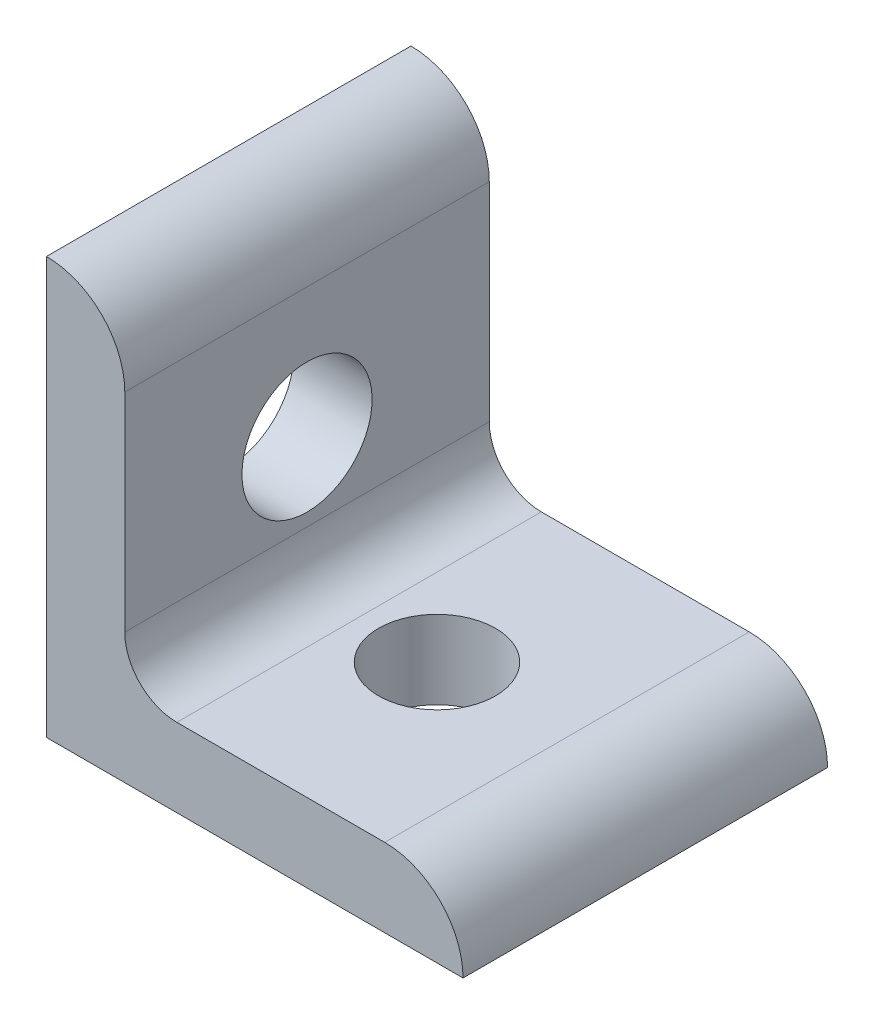
SolidWorks part; units mm, degrees
ref_plane "Front Plane" through (0, 0, 0) normal (0, 0, 1) x (1, 0, 0)
ref_plane "Top Plane" through (0, 0, 0) normal (0, 1, 0) x (1, 0, 0)
ref_plane "Right Plane" through (0, 0, 0) normal (1, 0, 0) x (0, 0, -1)
sketch "Sketch1" plane through (0, 0, 0) normal (0, 0, 1) x (1, 0, 0)
  line L0 (0, 0) -> (0, 25.4)
  line L1 (4.7752, 20.6248) -> (4.7752, 25.4) construction
  line L2 (4.7752, 20.6248) -> (4.7752, 7.9502)
  line L3 (7.9502, 4.7752) -> (20.6248, 4.7752)
  line L4 (4.7752, 25.4) -> (0, 25.4) construction
  line L5 (25.4, 0) -> (0, 0)
  line L6 (20.6248, 4.7752) -> (25.4, 4.7752) construction
  line L7 (25.4, 4.7752) -> (25.4, 0) construction
  arc A0 (4.7752, 20.6248) -> (0, 25.4) centre (0, 20.6248) ccw
  arc A1 (25.4, 0) -> (20.6248, 4.7752) centre (20.6248, 0) ccw
  arc A2 (4.7752, 7.9502) -> (7.9502, 4.7752) centre (7.9502, 7.9502) ccw
  point P10 (4.7752, 23.0124)
  dimension "E" = 3.175
  dimension "D" = 4.7752
  dimension "C" = 25.4
  dimension "B" = 25.4
extrude "Boss-Extrude1" add sketch "Sketch1" along normal mid plane 22.225
sketch "Sketch2" plane through (0, 0, 0) normal (0, 1, 0) x (1, 0, 0)
  line L0 (0, 0) -> (12.7, 0) construction
  circle A0 centre (12.7, 0) radius 3.5687
extrude "Cut-Extrude1" cut sketch "Sketch2" along normal through all
sketch "Sketch3" plane through (0, 0, 0) normal (1, 0, 0) x (0, 0, -1)
  line L0 (0, 0) -> (0, 12.7) construction
  circle A0 centre (0, 12.7) radius 3.5687
  dimension "D1" = 12.7
extrude "Cut-Extrude2" cut sketch "Sketch3" along normal through all
hole_wizard "3/8-16 Tapped Hole1" positions "Sketch4" profile "Sketch5" tap size "3/8-16" standard "ANSI Inch"
sketch "Sketch4" plane through (0, 0, 0) normal (-1, 0, 0) x (0, 0, 1)
  point P0 (0, 12.7)
sketch "Sketch5" plane through (0, 12.7, 0) normal (0, 1, 0) x (0, 0, 1)
  line L0 (0, 0) -> (0, 26.1972)
  line L1 (0, 26.1972) -> (3.9687, 23.8125)
  line L2 (3.9687, 23.8125) -> (3.9687, 0)
  line L5 (3.9687, 0) -> (0, 0)
  line L10 (0, 26.1972) -> (-3.9687, 23.8125) construction
  line L11 (0, -6.35) -> (0, 107.95) construction
  dimension "Tap Drill Dia." = 7.9375
  dimension "Tap Drill Depth" = 23.8125
  dimension "Drill Angle" = 118
cosmetic thread "Hole Thread1" parameters "D1"=4.7752, "D2"=9.525
equation "\"E@Sketch3\" = \"E@Sketch2\""
equation "\"D1@Sketch3\" = \"D1@Sketch2\""
